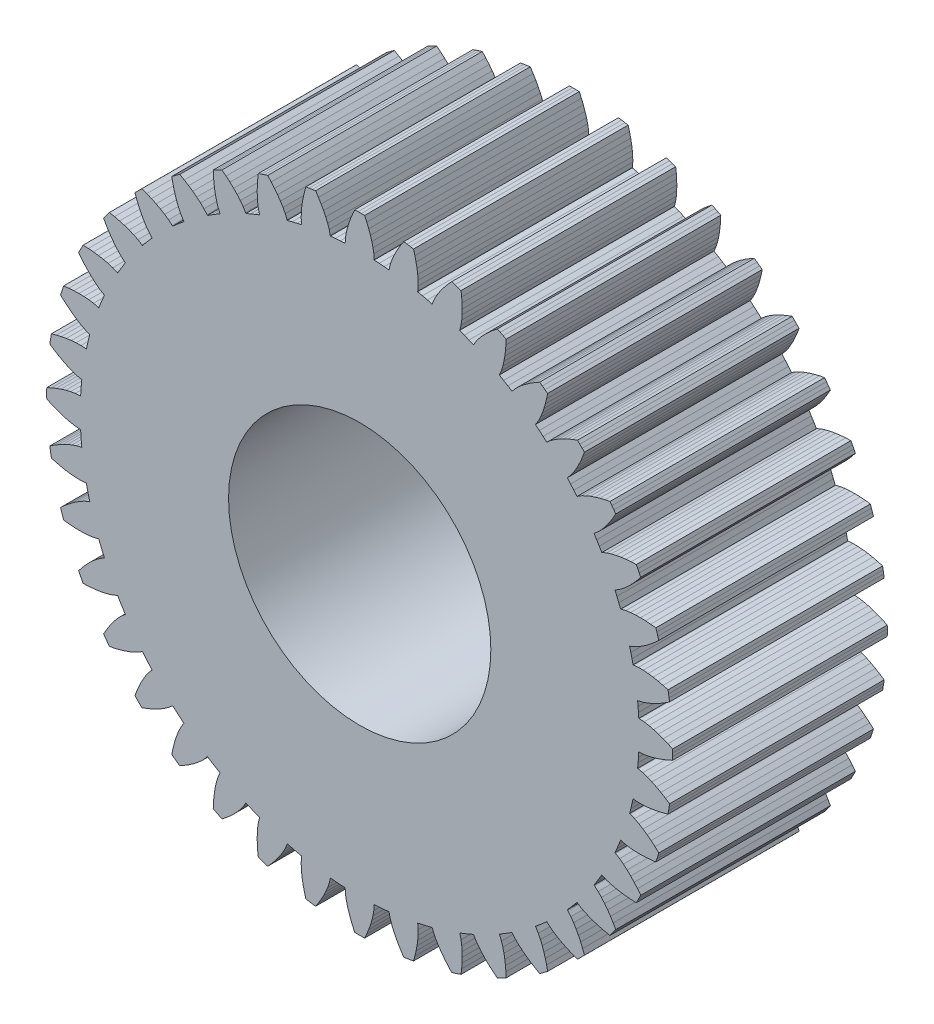
SolidWorks part; units mm, degrees
ref_plane "Спереди" through (0, 0, 0) normal (0, 0, 1) x (1, 0, 0)
ref_plane "Сверху" through (0, 0, 0) normal (0, 1, 0) x (1, 0, 0)
ref_plane "Справа" through (0, 0, 0) normal (1, 0, 0) x (0, 0, -1)
sketch "Эскиз1" plane through (0, 0, 0) normal (0, 0, 1) x (1, 0, 0)
  line L0 (23.4061, -1.2129) -> (23.4608, -1.2158)
  line L1 (23.4608, -1.2158) -> (23.8567, -1.1877)
  line L2 (23.8567, -1.1877) -> (24.2545, -1.1182)
  line L3 (24.2545, -1.1182) -> (24.6531, -1.0204)
  line L4 (24.6531, -1.0204) -> (25.052, -0.8989)
  line L5 (25.052, -0.8989) -> (25.4509, -0.7561)
  line L6 (25.4509, -0.7561) -> (25.8492, -0.5936)
  line L7 (25.8492, -0.5936) -> (26.2468, -0.4124)
  line L8 (26.2468, -0.4124) -> (26.2496, -0.1375)
  line L9 (26.2496, -0.1375) -> (26.2496, 0.1375)
  line L10 (26.2496, 0.1375) -> (26.2468, 0.4124)
  line L11 (26.2468, 0.4124) -> (25.8492, 0.5936)
  line L12 (25.8492, 0.5936) -> (25.4509, 0.7561)
  line L13 (25.4509, 0.7561) -> (25.052, 0.8989)
  line L14 (25.052, 0.8989) -> (24.6531, 1.0204)
  line L15 (24.6531, 1.0204) -> (24.2545, 1.1182)
  line L16 (24.2545, 1.1182) -> (23.8567, 1.1877)
  line L17 (23.8567, 1.1877) -> (23.4608, 1.2158)
  line L18 (23.4608, 1.2158) -> (23.4061, 1.2129)
  line L19 (23.4061, 1.2129) -> (23.3807, 1.6304)
  line L20 (23.3807, 1.6304) -> (23.3479, 2.0473)
  line L21 (23.3479, 2.0473) -> (23.3077, 2.4635)
  line L22 (23.3077, 2.4635) -> (23.3622, 2.4693)
  line L23 (23.3622, 2.4693) -> (23.7488, 2.559)
  line L24 (23.7488, 2.559) -> (24.1308, 2.6898)
  line L25 (24.1308, 2.6898) -> (24.5092, 2.8487)
  line L26 (24.5092, 2.8487) -> (24.8842, 3.0311)
  line L27 (24.8842, 3.0311) -> (25.2558, 3.2346)
  line L28 (25.2558, 3.2346) -> (25.6238, 3.4574)
  line L29 (25.6238, 3.4574) -> (25.9881, 3.6986)
  line L30 (25.9881, 3.6986) -> (25.948, 3.9706)
  line L31 (25.948, 3.9706) -> (25.905, 4.2421)
  line L32 (25.905, 4.2421) -> (25.8591, 4.5132)
  line L33 (25.8591, 4.5132) -> (25.4381, 4.63)
  line L34 (25.4381, 4.63) -> (25.0192, 4.7282)
  line L35 (25.0192, 4.7282) -> (24.603, 4.8069)
  line L36 (24.603, 4.8069) -> (24.1899, 4.8645)
  line L37 (24.1899, 4.8645) -> (23.7809, 4.8986)
  line L38 (23.7809, 4.8986) -> (23.3772, 4.9051)
  line L39 (23.3772, 4.9051) -> (22.9818, 4.8709)
  line L40 (22.9818, 4.8709) -> (22.9282, 4.8595)
  line L41 (22.9282, 4.8595) -> (22.8378, 5.2678)
  line L42 (22.8378, 5.2678) -> (22.7402, 5.6745)
  line L43 (22.7402, 5.6745) -> (22.6353, 6.0793)
  line L44 (22.6353, 6.0793) -> (22.6883, 6.0935)
  line L45 (22.6883, 6.0935) -> (23.0561, 6.2426)
  line L46 (23.0561, 6.2426) -> (23.4129, 6.4316)
  line L47 (23.4129, 6.4316) -> (23.7618, 6.6477)
  line L48 (23.7618, 6.6477) -> (24.1037, 6.8865)
  line L49 (24.1037, 6.8865) -> (24.4389, 7.1456)
  line L50 (24.4389, 7.1456) -> (24.7675, 7.4233)
  line L51 (24.7675, 7.4233) -> (25.0896, 7.7185)
  line L52 (25.0896, 7.7185) -> (25.0074, 7.9808)
  line L53 (25.0074, 7.9808) -> (24.9224, 8.2423)
  line L54 (24.9224, 8.2423) -> (24.8347, 8.5029)
  line L55 (24.8347, 8.5029) -> (24.4007, 8.5524)
  line L56 (24.4007, 8.5524) -> (23.9715, 8.5839)
  line L57 (23.9715, 8.5839) -> (23.5481, 8.5964)
  line L58 (23.5481, 8.5964) -> (23.1311, 8.5887)
  line L59 (23.1311, 8.5887) -> (22.7218, 8.5585)
  line L60 (22.7218, 8.5585) -> (22.3221, 8.5017)
  line L61 (22.3221, 8.5017) -> (21.9369, 8.406)
  line L62 (21.9369, 8.406) -> (21.8857, 8.3864)
  line L63 (21.8857, 8.3864) -> (21.7326, 8.7756)
  line L64 (21.7326, 8.7756) -> (21.5725, 9.162)
  line L65 (21.5725, 9.162) -> (21.4056, 9.5454)
  line L66 (21.4056, 9.5454) -> (21.4557, 9.5678)
  line L67 (21.4557, 9.5678) -> (21.7957, 9.7725)
  line L68 (21.7957, 9.7725) -> (22.1185, 10.015)
  line L69 (22.1185, 10.015) -> (22.4293, 10.283)
  line L70 (22.4293, 10.283) -> (22.7296, 10.5724)
  line L71 (22.7296, 10.5724) -> (23.0202, 10.8807)
  line L72 (23.0202, 10.8807) -> (23.3013, 11.2064)
  line L73 (23.3013, 11.2064) -> (23.5733, 11.5483)
  line L74 (23.5733, 11.5483) -> (23.451, 11.7946)
  line L75 (23.451, 11.7946) -> (23.3262, 12.0396)
  line L76 (23.3262, 12.0396) -> (23.1988, 12.2832)
  line L77 (23.1988, 12.2832) -> (22.7624, 12.2642)
  line L78 (22.7624, 12.2642) -> (22.3336, 12.2282)
  line L79 (22.3336, 12.2282) -> (21.9134, 12.1743)
  line L80 (21.9134, 12.1743) -> (21.5028, 12.1015)
  line L81 (21.5028, 12.1015) -> (21.1032, 12.0076)
  line L82 (21.1032, 12.0076) -> (20.7173, 11.8889)
  line L83 (20.7173, 11.8889) -> (20.3518, 11.7342)
  line L84 (20.3518, 11.7342) -> (20.3043, 11.7069)
  line L85 (20.3043, 11.7069) -> (20.0922, 12.0673)
  line L86 (20.0922, 12.0673) -> (19.8737, 12.4239)
  line L87 (19.8737, 12.4239) -> (19.6489, 12.7765)
  line L88 (19.6489, 12.7765) -> (19.6948, 12.8064)
  line L89 (19.6948, 12.8064) -> (19.9986, 13.0618)
  line L90 (19.9986, 13.0618) -> (20.2795, 13.3518)
  line L91 (20.2795, 13.3518) -> (20.5446, 13.6652)
  line L92 (20.5446, 13.6652) -> (20.7959, 13.9979)
  line L93 (20.7959, 13.9979) -> (21.0346, 14.3479)
  line L94 (21.0346, 14.3479) -> (21.2614, 14.7136)
  line L95 (21.2614, 14.7136) -> (21.4765, 15.0938)
  line L96 (21.4765, 15.0938) -> (21.3172, 15.3179)
  line L97 (21.3172, 15.3179) -> (21.1556, 15.5404)
  line L98 (21.1556, 15.5404) -> (20.9917, 15.7611)
  line L99 (20.9917, 15.7611) -> (20.5636, 15.674)
  line L100 (20.5636, 15.674) -> (20.1457, 15.5714)
  line L101 (20.1457, 15.5714) -> (19.7391, 15.4525)
  line L102 (19.7391, 15.4525) -> (19.345, 15.3163)
  line L103 (19.345, 15.3163) -> (18.965, 15.161)
  line L104 (18.965, 15.161) -> (18.6024, 14.9835)
  line L105 (18.6024, 14.9835) -> (18.2656, 14.7735)
  line L106 (18.2656, 14.7735) -> (18.223, 14.739)
  line L107 (18.223, 14.739) -> (17.9571, 15.0618)
  line L108 (17.9571, 15.0618) -> (17.6855, 15.3798)
  line L109 (17.6855, 15.3798) -> (17.4083, 15.6929)
  line L110 (17.4083, 15.6929) -> (17.449, 15.7296)
  line L111 (17.449, 15.7296) -> (17.7091, 16.0294)
  line L112 (17.7091, 16.0294) -> (17.9412, 16.3598)
  line L113 (17.9412, 16.3598) -> (18.1539, 16.7108)
  line L114 (18.1539, 16.7108) -> (18.3501, 17.0788)
  line L115 (18.3501, 17.0788) -> (18.5311, 17.4618)
  line L116 (18.5311, 17.4618) -> (18.6979, 17.8584)
  line L117 (18.6979, 17.8584) -> (18.8509, 18.2677)
  line L118 (18.8509, 18.2677) -> (18.6585, 18.4641)
  line L119 (18.6585, 18.4641) -> (18.4641, 18.6585)
  line L120 (18.4641, 18.6585) -> (18.2677, 18.8509)
  line L121 (18.2677, 18.8509) -> (17.8584, 18.6979)
  line L122 (17.8584, 18.6979) -> (17.4618, 18.5311)
  line L123 (17.4618, 18.5311) -> (17.0788, 18.3501)
  line L124 (17.0788, 18.3501) -> (16.7108, 18.1539)
  line L125 (16.7108, 18.1539) -> (16.3598, 17.9412)
  line L126 (16.3598, 17.9412) -> (16.0294, 17.7091)
  line L127 (16.0294, 17.7091) -> (15.7296, 17.449)
  line L128 (15.7296, 17.449) -> (15.6929, 17.4083)
  line L129 (15.6929, 17.4083) -> (15.3798, 17.6855)
  line L130 (15.3798, 17.6855) -> (15.0618, 17.9571)
  line L131 (15.0618, 17.9571) -> (14.739, 18.223)
  line L132 (14.739, 18.223) -> (14.7735, 18.2656)
  line L133 (14.7735, 18.2656) -> (14.9835, 18.6024)
  line L134 (14.9835, 18.6024) -> (15.161, 18.965)
  line L135 (15.161, 18.965) -> (15.3163, 19.345)
  line L136 (15.3163, 19.345) -> (15.4525, 19.7391)
  line L137 (15.4525, 19.7391) -> (15.5714, 20.1457)
  line L138 (15.5714, 20.1457) -> (15.674, 20.5636)
  line L139 (15.674, 20.5636) -> (15.7611, 20.9917)
  line L140 (15.7611, 20.9917) -> (15.5404, 21.1556)
  line L141 (15.5404, 21.1556) -> (15.3179, 21.3172)
  line L142 (15.3179, 21.3172) -> (15.0938, 21.4765)
  line L143 (15.0938, 21.4765) -> (14.7136, 21.2614)
  line L144 (14.7136, 21.2614) -> (14.3479, 21.0346)
  line L145 (14.3479, 21.0346) -> (13.9979, 20.7959)
  line L146 (13.9979, 20.7959) -> (13.6652, 20.5446)
  line L147 (13.6652, 20.5446) -> (13.3518, 20.2795)
  line L148 (13.3518, 20.2795) -> (13.0618, 19.9986)
  line L149 (13.0618, 19.9986) -> (12.8064, 19.6948)
  line L150 (12.8064, 19.6948) -> (12.7765, 19.6489)
  line L151 (12.7765, 19.6489) -> (12.4239, 19.8737)
  line L152 (12.4239, 19.8737) -> (12.0673, 20.0922)
  line L153 (12.0673, 20.0922) -> (11.7069, 20.3043)
  line L154 (11.7069, 20.3043) -> (11.7342, 20.3518)
  line L155 (11.7342, 20.3518) -> (11.8889, 20.7173)
  line L156 (11.8889, 20.7173) -> (12.0076, 21.1032)
  line L157 (12.0076, 21.1032) -> (12.1015, 21.5028)
  line L158 (12.1015, 21.5028) -> (12.1743, 21.9134)
  line L159 (12.1743, 21.9134) -> (12.2282, 22.3336)
  line L160 (12.2282, 22.3336) -> (12.2642, 22.7624)
  line L161 (12.2642, 22.7624) -> (12.2832, 23.1988)
  line L162 (12.2832, 23.1988) -> (12.0396, 23.3262)
  line L163 (12.0396, 23.3262) -> (11.7946, 23.451)
  line L164 (11.7946, 23.451) -> (11.5483, 23.5733)
  line L165 (11.5483, 23.5733) -> (11.2064, 23.3013)
  line L166 (11.2064, 23.3013) -> (10.8807, 23.0202)
  line L167 (10.8807, 23.0202) -> (10.5724, 22.7296)
  line L168 (10.5724, 22.7296) -> (10.283, 22.4293)
  line L169 (10.283, 22.4293) -> (10.015, 22.1185)
  line L170 (10.015, 22.1185) -> (9.7725, 21.7957)
  line L171 (9.7725, 21.7957) -> (9.5678, 21.4557)
  line L172 (9.5678, 21.4557) -> (9.5454, 21.4056)
  line L173 (9.5454, 21.4056) -> (9.162, 21.5725)
  line L174 (9.162, 21.5725) -> (8.7756, 21.7326)
  line L175 (8.7756, 21.7326) -> (8.3864, 21.8857)
  line L176 (8.3864, 21.8857) -> (8.406, 21.9369)
  line L177 (8.406, 21.9369) -> (8.5017, 22.3221)
  line L178 (8.5017, 22.3221) -> (8.5585, 22.7218)
  line L179 (8.5585, 22.7218) -> (8.5887, 23.1311)
  line L180 (8.5887, 23.1311) -> (8.5964, 23.5481)
  line L181 (8.5964, 23.5481) -> (8.5839, 23.9715)
  line L182 (8.5839, 23.9715) -> (8.5524, 24.4007)
  line L183 (8.5524, 24.4007) -> (8.5029, 24.8347)
  line L184 (8.5029, 24.8347) -> (8.2423, 24.9224)
  line L185 (8.2423, 24.9224) -> (7.9808, 25.0074)
  line L186 (7.9808, 25.0074) -> (7.7185, 25.0896)
  line L187 (7.7185, 25.0896) -> (7.4233, 24.7675)
  line L188 (7.4233, 24.7675) -> (7.1456, 24.4389)
  line L189 (7.1456, 24.4389) -> (6.8865, 24.1037)
  line L190 (6.8865, 24.1037) -> (6.6477, 23.7618)
  line L191 (6.6477, 23.7618) -> (6.4316, 23.4129)
  line L192 (6.4316, 23.4129) -> (6.2426, 23.0561)
  line L193 (6.2426, 23.0561) -> (6.0935, 22.6883)
  line L194 (6.0935, 22.6883) -> (6.0793, 22.6353)
  line L195 (6.0793, 22.6353) -> (5.6745, 22.7402)
  line L196 (5.6745, 22.7402) -> (5.2678, 22.8378)
  line L197 (5.2678, 22.8378) -> (4.8595, 22.9282)
  line L198 (4.8595, 22.9282) -> (4.8709, 22.9818)
  line L199 (4.8709, 22.9818) -> (4.9051, 23.3772)
  line L200 (4.9051, 23.3772) -> (4.8986, 23.7809)
  line L201 (4.8986, 23.7809) -> (4.8645, 24.1899)
  line L202 (4.8645, 24.1899) -> (4.8069, 24.603)
  line L203 (4.8069, 24.603) -> (4.7282, 25.0192)
  line L204 (4.7282, 25.0192) -> (4.63, 25.4381)
  line L205 (4.63, 25.4381) -> (4.5132, 25.8591)
  line L206 (4.5132, 25.8591) -> (4.2421, 25.905)
  line L207 (4.2421, 25.905) -> (3.9706, 25.948)
  line L208 (3.9706, 25.948) -> (3.6986, 25.9881)
  line L209 (3.6986, 25.9881) -> (3.4574, 25.6238)
  line L210 (3.4574, 25.6238) -> (3.2346, 25.2558)
  line L211 (3.2346, 25.2558) -> (3.0311, 24.8842)
  line L212 (3.0311, 24.8842) -> (2.8487, 24.5092)
  line L213 (2.8487, 24.5092) -> (2.6898, 24.1308)
  line L214 (2.6898, 24.1308) -> (2.559, 23.7488)
  line L215 (2.559, 23.7488) -> (2.4693, 23.3622)
  line L216 (2.4693, 23.3622) -> (2.4635, 23.3077)
  line L217 (2.4635, 23.3077) -> (2.0473, 23.3479)
  line L218 (2.0473, 23.3479) -> (1.6304, 23.3807)
  line L219 (1.6304, 23.3807) -> (1.2129, 23.4061)
  line L220 (1.2129, 23.4061) -> (1.2158, 23.4608)
  line L221 (1.2158, 23.4608) -> (1.1877, 23.8567)
  line L222 (1.1877, 23.8567) -> (1.1182, 24.2545)
  line L223 (1.1182, 24.2545) -> (1.0204, 24.6531)
  line L224 (1.0204, 24.6531) -> (0.8989, 25.052)
  line L225 (0.8989, 25.052) -> (0.7561, 25.4509)
  line L226 (0.7561, 25.4509) -> (0.5936, 25.8492)
  line L227 (0.5936, 25.8492) -> (0.4124, 26.2468)
  line L228 (0.4124, 26.2468) -> (0.1375, 26.2496)
  line L229 (0.1375, 26.2496) -> (-0.1375, 26.2496)
  line L230 (-0.1375, 26.2496) -> (-0.4124, 26.2468)
  line L231 (-0.4124, 26.2468) -> (-0.5936, 25.8492)
  line L232 (-0.5936, 25.8492) -> (-0.7561, 25.4509)
  line L233 (-0.7561, 25.4509) -> (-0.8989, 25.052)
  line L234 (-0.8989, 25.052) -> (-1.0204, 24.6531)
  line L235 (-1.0204, 24.6531) -> (-1.1182, 24.2545)
  line L236 (-1.1182, 24.2545) -> (-1.1877, 23.8567)
  line L237 (-1.1877, 23.8567) -> (-1.2158, 23.4608)
  line L238 (-1.2158, 23.4608) -> (-1.2129, 23.4061)
  line L239 (-1.2129, 23.4061) -> (-1.6304, 23.3807)
  line L240 (-1.6304, 23.3807) -> (-2.0473, 23.3479)
  line L241 (-2.0473, 23.3479) -> (-2.4635, 23.3077)
  line L242 (-2.4635, 23.3077) -> (-2.4693, 23.3622)
  line L243 (-2.4693, 23.3622) -> (-2.559, 23.7488)
  line L244 (-2.559, 23.7488) -> (-2.6898, 24.1308)
  line L245 (-2.6898, 24.1308) -> (-2.8487, 24.5092)
  line L246 (-2.8487, 24.5092) -> (-3.0311, 24.8842)
  line L247 (-3.0311, 24.8842) -> (-3.2346, 25.2558)
  line L248 (-3.2346, 25.2558) -> (-3.4574, 25.6238)
  line L249 (-3.4574, 25.6238) -> (-3.6986, 25.9881)
  line L250 (-3.6986, 25.9881) -> (-3.9706, 25.948)
  line L251 (-3.9706, 25.948) -> (-4.2421, 25.905)
  line L252 (-4.2421, 25.905) -> (-4.5132, 25.8591)
  line L253 (-4.5132, 25.8591) -> (-4.63, 25.4381)
  line L254 (-4.63, 25.4381) -> (-4.7282, 25.0192)
  line L255 (-4.7282, 25.0192) -> (-4.8069, 24.603)
  line L256 (-4.8069, 24.603) -> (-4.8645, 24.1899)
  line L257 (-4.8645, 24.1899) -> (-4.8986, 23.7809)
  line L258 (-4.8986, 23.7809) -> (-4.9051, 23.3772)
  line L259 (-4.9051, 23.3772) -> (-4.8709, 22.9818)
  line L260 (-4.8709, 22.9818) -> (-4.8595, 22.9282)
  line L261 (-4.8595, 22.9282) -> (-5.2678, 22.8378)
  line L262 (-5.2678, 22.8378) -> (-5.6745, 22.7402)
  line L263 (-5.6745, 22.7402) -> (-6.0793, 22.6353)
  line L264 (-6.0793, 22.6353) -> (-6.0935, 22.6883)
  line L265 (-6.0935, 22.6883) -> (-6.2426, 23.0561)
  line L266 (-6.2426, 23.0561) -> (-6.4316, 23.4129)
  line L267 (-6.4316, 23.4129) -> (-6.6477, 23.7618)
  line L268 (-6.6477, 23.7618) -> (-6.8865, 24.1037)
  line L269 (-6.8865, 24.1037) -> (-7.1456, 24.4389)
  line L270 (-7.1456, 24.4389) -> (-7.4233, 24.7675)
  line L271 (-7.4233, 24.7675) -> (-7.7185, 25.0896)
  line L272 (-7.7185, 25.0896) -> (-7.9808, 25.0074)
  line L273 (-7.9808, 25.0074) -> (-8.2423, 24.9224)
  line L274 (-8.2423, 24.9224) -> (-8.5029, 24.8347)
  line L275 (-8.5029, 24.8347) -> (-8.5524, 24.4007)
  line L276 (-8.5524, 24.4007) -> (-8.5839, 23.9715)
  line L277 (-8.5839, 23.9715) -> (-8.5964, 23.5481)
  line L278 (-8.5964, 23.5481) -> (-8.5887, 23.1311)
  line L279 (-8.5887, 23.1311) -> (-8.5585, 22.7218)
  line L280 (-8.5585, 22.7218) -> (-8.5017, 22.3221)
  line L281 (-8.5017, 22.3221) -> (-8.406, 21.9369)
  line L282 (-8.406, 21.9369) -> (-8.3864, 21.8857)
  line L283 (-8.3864, 21.8857) -> (-8.7756, 21.7326)
  line L284 (-8.7756, 21.7326) -> (-9.162, 21.5725)
  line L285 (-9.162, 21.5725) -> (-9.5454, 21.4056)
  line L286 (-9.5454, 21.4056) -> (-9.5678, 21.4557)
  line L287 (-9.5678, 21.4557) -> (-9.7725, 21.7957)
  line L288 (-9.7725, 21.7957) -> (-10.015, 22.1185)
  line L289 (-10.015, 22.1185) -> (-10.283, 22.4293)
  line L290 (-10.283, 22.4293) -> (-10.5724, 22.7296)
  line L291 (-10.5724, 22.7296) -> (-10.8807, 23.0202)
  line L292 (-10.8807, 23.0202) -> (-11.2064, 23.3013)
  line L293 (-11.2064, 23.3013) -> (-11.5483, 23.5733)
  line L294 (-11.5483, 23.5733) -> (-11.7946, 23.451)
  line L295 (-11.7946, 23.451) -> (-12.0396, 23.3262)
  line L296 (-12.0396, 23.3262) -> (-12.2832, 23.1988)
  line L297 (-12.2832, 23.1988) -> (-12.2642, 22.7624)
  line L298 (-12.2642, 22.7624) -> (-12.2282, 22.3336)
  line L299 (-12.2282, 22.3336) -> (-12.1743, 21.9134)
  line L300 (-12.1743, 21.9134) -> (-12.1015, 21.5028)
  line L301 (-12.1015, 21.5028) -> (-12.0076, 21.1032)
  line L302 (-12.0076, 21.1032) -> (-11.8889, 20.7173)
  line L303 (-11.8889, 20.7173) -> (-11.7342, 20.3518)
  line L304 (-11.7342, 20.3518) -> (-11.7069, 20.3043)
  line L305 (-11.7069, 20.3043) -> (-12.0673, 20.0922)
  line L306 (-12.0673, 20.0922) -> (-12.4239, 19.8737)
  line L307 (-12.4239, 19.8737) -> (-12.7765, 19.6489)
  line L308 (-12.7765, 19.6489) -> (-12.8064, 19.6948)
  line L309 (-12.8064, 19.6948) -> (-13.0618, 19.9986)
  line L310 (-13.0618, 19.9986) -> (-13.3518, 20.2795)
  line L311 (-13.3518, 20.2795) -> (-13.6652, 20.5446)
  line L312 (-13.6652, 20.5446) -> (-13.9979, 20.7959)
  line L313 (-13.9979, 20.7959) -> (-14.3479, 21.0346)
  line L314 (-14.3479, 21.0346) -> (-14.7136, 21.2614)
  line L315 (-14.7136, 21.2614) -> (-15.0938, 21.4765)
  line L316 (-15.0938, 21.4765) -> (-15.3179, 21.3172)
  line L317 (-15.3179, 21.3172) -> (-15.5404, 21.1556)
  line L318 (-15.5404, 21.1556) -> (-15.7611, 20.9917)
  line L319 (-15.7611, 20.9917) -> (-15.674, 20.5636)
  line L320 (-15.674, 20.5636) -> (-15.5714, 20.1457)
  line L321 (-15.5714, 20.1457) -> (-15.4525, 19.7391)
  line L322 (-15.4525, 19.7391) -> (-15.3163, 19.345)
  line L323 (-15.3163, 19.345) -> (-15.161, 18.965)
  line L324 (-15.161, 18.965) -> (-14.9835, 18.6024)
  line L325 (-14.9835, 18.6024) -> (-14.7735, 18.2656)
  line L326 (-14.7735, 18.2656) -> (-14.739, 18.223)
  line L327 (-14.739, 18.223) -> (-15.0618, 17.9571)
  line L328 (-15.0618, 17.9571) -> (-15.3798, 17.6855)
  line L329 (-15.3798, 17.6855) -> (-15.6929, 17.4083)
  line L330 (-15.6929, 17.4083) -> (-15.7296, 17.449)
  line L331 (-15.7296, 17.449) -> (-16.0294, 17.7091)
  line L332 (-16.0294, 17.7091) -> (-16.3598, 17.9412)
  line L333 (-16.3598, 17.9412) -> (-16.7108, 18.1539)
  line L334 (-16.7108, 18.1539) -> (-17.0788, 18.3501)
  line L335 (-17.0788, 18.3501) -> (-17.4618, 18.5311)
  line L336 (-17.4618, 18.5311) -> (-17.8584, 18.6979)
  line L337 (-17.8584, 18.6979) -> (-18.2677, 18.8509)
  line L338 (-18.2677, 18.8509) -> (-18.4641, 18.6585)
  line L339 (-18.4641, 18.6585) -> (-18.6585, 18.4641)
  line L340 (-18.6585, 18.4641) -> (-18.8509, 18.2677)
  line L341 (-18.8509, 18.2677) -> (-18.6979, 17.8584)
  line L342 (-18.6979, 17.8584) -> (-18.5311, 17.4618)
  line L343 (-18.5311, 17.4618) -> (-18.3501, 17.0788)
  line L344 (-18.3501, 17.0788) -> (-18.1539, 16.7108)
  line L345 (-18.1539, 16.7108) -> (-17.9412, 16.3598)
  line L346 (-17.9412, 16.3598) -> (-17.7091, 16.0294)
  line L347 (-17.7091, 16.0294) -> (-17.449, 15.7296)
  line L348 (-17.449, 15.7296) -> (-17.4083, 15.6929)
  line L349 (-17.4083, 15.6929) -> (-17.6855, 15.3798)
  line L350 (-17.6855, 15.3798) -> (-17.9571, 15.0618)
  line L351 (-17.9571, 15.0618) -> (-18.223, 14.739)
  line L352 (-18.223, 14.739) -> (-18.2656, 14.7735)
  line L353 (-18.2656, 14.7735) -> (-18.6024, 14.9835)
  line L354 (-18.6024, 14.9835) -> (-18.965, 15.161)
  line L355 (-18.965, 15.161) -> (-19.345, 15.3163)
  line L356 (-19.345, 15.3163) -> (-19.7391, 15.4525)
  line L357 (-19.7391, 15.4525) -> (-20.1457, 15.5714)
  line L358 (-20.1457, 15.5714) -> (-20.5636, 15.674)
  line L359 (-20.5636, 15.674) -> (-20.9917, 15.7611)
  line L360 (-20.9917, 15.7611) -> (-21.1556, 15.5404)
  line L361 (-21.1556, 15.5404) -> (-21.3172, 15.3179)
  line L362 (-21.3172, 15.3179) -> (-21.4765, 15.0938)
  line L363 (-21.4765, 15.0938) -> (-21.2614, 14.7136)
  line L364 (-21.2614, 14.7136) -> (-21.0346, 14.3479)
  line L365 (-21.0346, 14.3479) -> (-20.7959, 13.9979)
  line L366 (-20.7959, 13.9979) -> (-20.5446, 13.6652)
  line L367 (-20.5446, 13.6652) -> (-20.2795, 13.3518)
  line L368 (-20.2795, 13.3518) -> (-19.9986, 13.0618)
  line L369 (-19.9986, 13.0618) -> (-19.6948, 12.8064)
  line L370 (-19.6948, 12.8064) -> (-19.6489, 12.7765)
  line L371 (-19.6489, 12.7765) -> (-19.8737, 12.4239)
  line L372 (-19.8737, 12.4239) -> (-20.0922, 12.0673)
  line L373 (-20.0922, 12.0673) -> (-20.3043, 11.7069)
  line L374 (-20.3043, 11.7069) -> (-20.3518, 11.7342)
  line L375 (-20.3518, 11.7342) -> (-20.7173, 11.8889)
  line L376 (-20.7173, 11.8889) -> (-21.1032, 12.0076)
  line L377 (-21.1032, 12.0076) -> (-21.5028, 12.1015)
  line L378 (-21.5028, 12.1015) -> (-21.9134, 12.1743)
  line L379 (-21.9134, 12.1743) -> (-22.3336, 12.2282)
  line L380 (-22.3336, 12.2282) -> (-22.7624, 12.2642)
  line L381 (-22.7624, 12.2642) -> (-23.1988, 12.2832)
  line L382 (-23.1988, 12.2832) -> (-23.3262, 12.0396)
  line L383 (-23.3262, 12.0396) -> (-23.451, 11.7946)
  line L384 (-23.451, 11.7946) -> (-23.5733, 11.5483)
  line L385 (-23.5733, 11.5483) -> (-23.3013, 11.2064)
  line L386 (-23.3013, 11.2064) -> (-23.0202, 10.8807)
  line L387 (-23.0202, 10.8807) -> (-22.7296, 10.5724)
  line L388 (-22.7296, 10.5724) -> (-22.4293, 10.283)
  line L389 (-22.4293, 10.283) -> (-22.1185, 10.015)
  line L390 (-22.1185, 10.015) -> (-21.7957, 9.7725)
  line L391 (-21.7957, 9.7725) -> (-21.4557, 9.5678)
  line L392 (-21.4557, 9.5678) -> (-21.4056, 9.5454)
  line L393 (-21.4056, 9.5454) -> (-21.5725, 9.162)
  line L394 (-21.5725, 9.162) -> (-21.7326, 8.7756)
  line L395 (-21.7326, 8.7756) -> (-21.8857, 8.3864)
  line L396 (-21.8857, 8.3864) -> (-21.9369, 8.406)
  line L397 (-21.9369, 8.406) -> (-22.3221, 8.5017)
  line L398 (-22.3221, 8.5017) -> (-22.7218, 8.5585)
  line L399 (-22.7218, 8.5585) -> (-23.1311, 8.5887)
  line L400 (-23.1311, 8.5887) -> (-23.5481, 8.5964)
  line L401 (-23.5481, 8.5964) -> (-23.9715, 8.5839)
  line L402 (-23.9715, 8.5839) -> (-24.4007, 8.5524)
  line L403 (-24.4007, 8.5524) -> (-24.8347, 8.5029)
  line L404 (-24.8347, 8.5029) -> (-24.9224, 8.2423)
  line L405 (-24.9224, 8.2423) -> (-25.0074, 7.9808)
  line L406 (-25.0074, 7.9808) -> (-25.0896, 7.7185)
  line L407 (-25.0896, 7.7185) -> (-24.7675, 7.4233)
  line L408 (-24.7675, 7.4233) -> (-24.4389, 7.1456)
  line L409 (-24.4389, 7.1456) -> (-24.1037, 6.8865)
  line L410 (-24.1037, 6.8865) -> (-23.7618, 6.6477)
  line L411 (-23.7618, 6.6477) -> (-23.4129, 6.4316)
  line L412 (-23.4129, 6.4316) -> (-23.0561, 6.2426)
  line L413 (-23.0561, 6.2426) -> (-22.6883, 6.0935)
  line L414 (-22.6883, 6.0935) -> (-22.6353, 6.0793)
  line L415 (-22.6353, 6.0793) -> (-22.7402, 5.6745)
  line L416 (-22.7402, 5.6745) -> (-22.8378, 5.2678)
  line L417 (-22.8378, 5.2678) -> (-22.9282, 4.8595)
  line L418 (-22.9282, 4.8595) -> (-22.9818, 4.8709)
  line L419 (-22.9818, 4.8709) -> (-23.3772, 4.9051)
  line L420 (-23.3772, 4.9051) -> (-23.7809, 4.8986)
  line L421 (-23.7809, 4.8986) -> (-24.1899, 4.8645)
  line L422 (-24.1899, 4.8645) -> (-24.603, 4.8069)
  line L423 (-24.603, 4.8069) -> (-25.0192, 4.7282)
  line L424 (-25.0192, 4.7282) -> (-25.4381, 4.63)
  line L425 (-25.4381, 4.63) -> (-25.8591, 4.5132)
  line L426 (-25.8591, 4.5132) -> (-25.905, 4.2421)
  line L427 (-25.905, 4.2421) -> (-25.948, 3.9706)
  line L428 (-25.948, 3.9706) -> (-25.9881, 3.6986)
  line L429 (-25.9881, 3.6986) -> (-25.6238, 3.4574)
  line L430 (-25.6238, 3.4574) -> (-25.2558, 3.2346)
  line L431 (-25.2558, 3.2346) -> (-24.8842, 3.0311)
  line L432 (-24.8842, 3.0311) -> (-24.5092, 2.8487)
  line L433 (-24.5092, 2.8487) -> (-24.1308, 2.6898)
  line L434 (-24.1308, 2.6898) -> (-23.7488, 2.559)
  line L435 (-23.7488, 2.559) -> (-23.3622, 2.4693)
  line L436 (-23.3622, 2.4693) -> (-23.3077, 2.4635)
  line L437 (-23.3077, 2.4635) -> (-23.3479, 2.0473)
  line L438 (-23.3479, 2.0473) -> (-23.3807, 1.6304)
  line L439 (-23.3807, 1.6304) -> (-23.4061, 1.2129)
  line L440 (-23.4061, 1.2129) -> (-23.4608, 1.2158)
  line L441 (-23.4608, 1.2158) -> (-23.8567, 1.1877)
  line L442 (-23.8567, 1.1877) -> (-24.2545, 1.1182)
  line L443 (-24.2545, 1.1182) -> (-24.6531, 1.0204)
  line L444 (-24.6531, 1.0204) -> (-25.052, 0.8989)
  line L445 (-25.052, 0.8989) -> (-25.4509, 0.7561)
  line L446 (-25.4509, 0.7561) -> (-25.8492, 0.5936)
  line L447 (-25.8492, 0.5936) -> (-26.2468, 0.4124)
  line L448 (-26.2468, 0.4124) -> (-26.2496, 0.1375)
  line L449 (-26.2496, 0.1375) -> (-26.2496, -0.1375)
  line L450 (-26.2496, -0.1375) -> (-26.2468, -0.4124)
  line L451 (-26.2468, -0.4124) -> (-25.8492, -0.5936)
  line L452 (-25.8492, -0.5936) -> (-25.4509, -0.7561)
  line L453 (-25.4509, -0.7561) -> (-25.052, -0.8989)
  line L454 (-25.052, -0.8989) -> (-24.6531, -1.0204)
  line L455 (-24.6531, -1.0204) -> (-24.2545, -1.1182)
  line L456 (-24.2545, -1.1182) -> (-23.8567, -1.1877)
  line L457 (-23.8567, -1.1877) -> (-23.4608, -1.2158)
  line L458 (-23.4608, -1.2158) -> (-23.4061, -1.2129)
  line L459 (-23.4061, -1.2129) -> (-23.3807, -1.6304)
  line L460 (-23.3807, -1.6304) -> (-23.3479, -2.0473)
  line L461 (-23.3479, -2.0473) -> (-23.3077, -2.4635)
  line L462 (-23.3077, -2.4635) -> (-23.3622, -2.4693)
  line L463 (-23.3622, -2.4693) -> (-23.7488, -2.559)
  line L464 (-23.7488, -2.559) -> (-24.1308, -2.6898)
  line L465 (-24.1308, -2.6898) -> (-24.5092, -2.8487)
  line L466 (-24.5092, -2.8487) -> (-24.8842, -3.0311)
  line L467 (-24.8842, -3.0311) -> (-25.2558, -3.2346)
  line L468 (-25.2558, -3.2346) -> (-25.6238, -3.4574)
  line L469 (-25.6238, -3.4574) -> (-25.9881, -3.6986)
  line L470 (-25.9881, -3.6986) -> (-25.948, -3.9706)
  line L471 (-25.948, -3.9706) -> (-25.905, -4.2421)
  line L472 (-25.905, -4.2421) -> (-25.8591, -4.5132)
  line L473 (-25.8591, -4.5132) -> (-25.4381, -4.63)
  line L474 (-25.4381, -4.63) -> (-25.0192, -4.7282)
  line L475 (-25.0192, -4.7282) -> (-24.603, -4.8069)
  line L476 (-24.603, -4.8069) -> (-24.1899, -4.8645)
  line L477 (-24.1899, -4.8645) -> (-23.7809, -4.8986)
  line L478 (-23.7809, -4.8986) -> (-23.3772, -4.9051)
  line L479 (-23.3772, -4.9051) -> (-22.9818, -4.8709)
  line L480 (-22.9818, -4.8709) -> (-22.9282, -4.8595)
  line L481 (-22.9282, -4.8595) -> (-22.8378, -5.2678)
  line L482 (-22.8378, -5.2678) -> (-22.7402, -5.6745)
  line L483 (-22.7402, -5.6745) -> (-22.6353, -6.0793)
  line L484 (-22.6353, -6.0793) -> (-22.6883, -6.0935)
  line L485 (-22.6883, -6.0935) -> (-23.0561, -6.2426)
  line L486 (-23.0561, -6.2426) -> (-23.4129, -6.4316)
  line L487 (-23.4129, -6.4316) -> (-23.7618, -6.6477)
  line L488 (-23.7618, -6.6477) -> (-24.1037, -6.8865)
  line L489 (-24.1037, -6.8865) -> (-24.4389, -7.1456)
  line L490 (-24.4389, -7.1456) -> (-24.7675, -7.4233)
  line L491 (-24.7675, -7.4233) -> (-25.0896, -7.7185)
  line L492 (-25.0896, -7.7185) -> (-25.0074, -7.9808)
  line L493 (-25.0074, -7.9808) -> (-24.9224, -8.2423)
  line L494 (-24.9224, -8.2423) -> (-24.8347, -8.5029)
  line L495 (-24.8347, -8.5029) -> (-24.4007, -8.5524)
  line L496 (-24.4007, -8.5524) -> (-23.9715, -8.5839)
  line L497 (-23.9715, -8.5839) -> (-23.5481, -8.5964)
  line L498 (-23.5481, -8.5964) -> (-23.1311, -8.5887)
  line L499 (-23.1311, -8.5887) -> (-22.7218, -8.5585)
  line L500 (-22.7218, -8.5585) -> (-22.3221, -8.5017)
  line L501 (-22.3221, -8.5017) -> (-21.9369, -8.406)
  line L502 (-21.9369, -8.406) -> (-21.8857, -8.3864)
  line L503 (-21.8857, -8.3864) -> (-21.7326, -8.7756)
  line L504 (-21.7326, -8.7756) -> (-21.5725, -9.162)
  line L505 (-21.5725, -9.162) -> (-21.4056, -9.5454)
  line L506 (-21.4056, -9.5454) -> (-21.4557, -9.5678)
  line L507 (-21.4557, -9.5678) -> (-21.7957, -9.7725)
  line L508 (-21.7957, -9.7725) -> (-22.1185, -10.015)
  line L509 (-22.1185, -10.015) -> (-22.4293, -10.283)
  line L510 (-22.4293, -10.283) -> (-22.7296, -10.5724)
  line L511 (-22.7296, -10.5724) -> (-23.0202, -10.8807)
  line L512 (-23.0202, -10.8807) -> (-23.3013, -11.2064)
  line L513 (-23.3013, -11.2064) -> (-23.5733, -11.5483)
  line L514 (-23.5733, -11.5483) -> (-23.451, -11.7946)
  line L515 (-23.451, -11.7946) -> (-23.3262, -12.0396)
  line L516 (-23.3262, -12.0396) -> (-23.1988, -12.2832)
  line L517 (-23.1988, -12.2832) -> (-22.7624, -12.2642)
  line L518 (-22.7624, -12.2642) -> (-22.3336, -12.2282)
  line L519 (-22.3336, -12.2282) -> (-21.9134, -12.1743)
  line L520 (-21.9134, -12.1743) -> (-21.5028, -12.1015)
  line L521 (-21.5028, -12.1015) -> (-21.1032, -12.0076)
  line L522 (-21.1032, -12.0076) -> (-20.7173, -11.8889)
  line L523 (-20.7173, -11.8889) -> (-20.3518, -11.7342)
  line L524 (-20.3518, -11.7342) -> (-20.3043, -11.7069)
  line L525 (-20.3043, -11.7069) -> (-20.0922, -12.0673)
  line L526 (-20.0922, -12.0673) -> (-19.8737, -12.4239)
  line L527 (-19.8737, -12.4239) -> (-19.6489, -12.7765)
  line L528 (-19.6489, -12.7765) -> (-19.6948, -12.8064)
  line L529 (-19.6948, -12.8064) -> (-19.9986, -13.0618)
  line L530 (-19.9986, -13.0618) -> (-20.2795, -13.3518)
  line L531 (-20.2795, -13.3518) -> (-20.5446, -13.6652)
  line L532 (-20.5446, -13.6652) -> (-20.7959, -13.9979)
  line L533 (-20.7959, -13.9979) -> (-21.0346, -14.3479)
  line L534 (-21.0346, -14.3479) -> (-21.2614, -14.7136)
  line L535 (-21.2614, -14.7136) -> (-21.4765, -15.0938)
  line L536 (-21.4765, -15.0938) -> (-21.3172, -15.3179)
  line L537 (-21.3172, -15.3179) -> (-21.1556, -15.5404)
  line L538 (-21.1556, -15.5404) -> (-20.9917, -15.7611)
  line L539 (-20.9917, -15.7611) -> (-20.5636, -15.674)
  line L540 (-20.5636, -15.674) -> (-20.1457, -15.5714)
  line L541 (-20.1457, -15.5714) -> (-19.7391, -15.4525)
  line L542 (-19.7391, -15.4525) -> (-19.345, -15.3163)
  line L543 (-19.345, -15.3163) -> (-18.965, -15.161)
  line L544 (-18.965, -15.161) -> (-18.6024, -14.9835)
  line L545 (-18.6024, -14.9835) -> (-18.2656, -14.7735)
  line L546 (-18.2656, -14.7735) -> (-18.223, -14.739)
  line L547 (-18.223, -14.739) -> (-17.9571, -15.0618)
  line L548 (-17.9571, -15.0618) -> (-17.6855, -15.3798)
  line L549 (-17.6855, -15.3798) -> (-17.4083, -15.6929)
  line L550 (-17.4083, -15.6929) -> (-17.449, -15.7296)
  line L551 (-17.449, -15.7296) -> (-17.7091, -16.0294)
  line L552 (-17.7091, -16.0294) -> (-17.9412, -16.3598)
  line L553 (-17.9412, -16.3598) -> (-18.1539, -16.7108)
  line L554 (-18.1539, -16.7108) -> (-18.3501, -17.0788)
  line L555 (-18.3501, -17.0788) -> (-18.5311, -17.4618)
  line L556 (-18.5311, -17.4618) -> (-18.6979, -17.8584)
  line L557 (-18.6979, -17.8584) -> (-18.8509, -18.2677)
  line L558 (-18.8509, -18.2677) -> (-18.6585, -18.4641)
  line L559 (-18.6585, -18.4641) -> (-18.4641, -18.6585)
  line L560 (-18.4641, -18.6585) -> (-18.2677, -18.8509)
  line L561 (-18.2677, -18.8509) -> (-17.8584, -18.6979)
  line L562 (-17.8584, -18.6979) -> (-17.4618, -18.5311)
  line L563 (-17.4618, -18.5311) -> (-17.0788, -18.3501)
  line L564 (-17.0788, -18.3501) -> (-16.7108, -18.1539)
  line L565 (-16.7108, -18.1539) -> (-16.3598, -17.9412)
  line L566 (-16.3598, -17.9412) -> (-16.0294, -17.7091)
  line L567 (-16.0294, -17.7091) -> (-15.7296, -17.449)
  line L568 (-15.7296, -17.449) -> (-15.6929, -17.4083)
  line L569 (-15.6929, -17.4083) -> (-15.3798, -17.6855)
  line L570 (-15.3798, -17.6855) -> (-15.0618, -17.9571)
  line L571 (-15.0618, -17.9571) -> (-14.739, -18.223)
  line L572 (-14.739, -18.223) -> (-14.7735, -18.2656)
  line L573 (-14.7735, -18.2656) -> (-14.9835, -18.6024)
  line L574 (-14.9835, -18.6024) -> (-15.161, -18.965)
  line L575 (-15.161, -18.965) -> (-15.3163, -19.345)
  line L576 (-15.3163, -19.345) -> (-15.4525, -19.7391)
  line L577 (-15.4525, -19.7391) -> (-15.5714, -20.1457)
  line L578 (-15.5714, -20.1457) -> (-15.674, -20.5636)
  line L579 (-15.674, -20.5636) -> (-15.7611, -20.9917)
  line L580 (-15.7611, -20.9917) -> (-15.5404, -21.1556)
  line L581 (-15.5404, -21.1556) -> (-15.3179, -21.3172)
  line L582 (-15.3179, -21.3172) -> (-15.0938, -21.4765)
  line L583 (-15.0938, -21.4765) -> (-14.7136, -21.2614)
  line L584 (-14.7136, -21.2614) -> (-14.3479, -21.0346)
  line L585 (-14.3479, -21.0346) -> (-13.9979, -20.7959)
  line L586 (-13.9979, -20.7959) -> (-13.6652, -20.5446)
  line L587 (-13.6652, -20.5446) -> (-13.3518, -20.2795)
  line L588 (-13.3518, -20.2795) -> (-13.0618, -19.9986)
  line L589 (-13.0618, -19.9986) -> (-12.8064, -19.6948)
  line L590 (-12.8064, -19.6948) -> (-12.7765, -19.6489)
  line L591 (-12.7765, -19.6489) -> (-12.4239, -19.8737)
  line L592 (-12.4239, -19.8737) -> (-12.0673, -20.0922)
  line L593 (-12.0673, -20.0922) -> (-11.7069, -20.3043)
  line L594 (-11.7069, -20.3043) -> (-11.7342, -20.3518)
  line L595 (-11.7342, -20.3518) -> (-11.8889, -20.7173)
  line L596 (-11.8889, -20.7173) -> (-12.0076, -21.1032)
  line L597 (-12.0076, -21.1032) -> (-12.1015, -21.5028)
  line L598 (-12.1015, -21.5028) -> (-12.1743, -21.9134)
  line L599 (-12.1743, -21.9134) -> (-12.2282, -22.3336)
  line L600 (-12.2282, -22.3336) -> (-12.2642, -22.7624)
  line L601 (-12.2642, -22.7624) -> (-12.2832, -23.1988)
  line L602 (-12.2832, -23.1988) -> (-12.0396, -23.3262)
  line L603 (-12.0396, -23.3262) -> (-11.7946, -23.451)
  line L604 (-11.7946, -23.451) -> (-11.5483, -23.5733)
  line L605 (-11.5483, -23.5733) -> (-11.2064, -23.3013)
  line L606 (-11.2064, -23.3013) -> (-10.8807, -23.0202)
  line L607 (-10.8807, -23.0202) -> (-10.5724, -22.7296)
  line L608 (-10.5724, -22.7296) -> (-10.283, -22.4293)
  line L609 (-10.283, -22.4293) -> (-10.015, -22.1185)
  line L610 (-10.015, -22.1185) -> (-9.7725, -21.7957)
  line L611 (-9.7725, -21.7957) -> (-9.5678, -21.4557)
  line L612 (-9.5678, -21.4557) -> (-9.5454, -21.4056)
  line L613 (-9.5454, -21.4056) -> (-9.162, -21.5725)
  line L614 (-9.162, -21.5725) -> (-8.7756, -21.7326)
  line L615 (-8.7756, -21.7326) -> (-8.3864, -21.8857)
  line L616 (-8.3864, -21.8857) -> (-8.406, -21.9369)
  line L617 (-8.406, -21.9369) -> (-8.5017, -22.3221)
  line L618 (-8.5017, -22.3221) -> (-8.5585, -22.7218)
  line L619 (-8.5585, -22.7218) -> (-8.5887, -23.1311)
  line L620 (-8.5887, -23.1311) -> (-8.5964, -23.5481)
  line L621 (-8.5964, -23.5481) -> (-8.5839, -23.9715)
  line L622 (-8.5839, -23.9715) -> (-8.5524, -24.4007)
  line L623 (-8.5524, -24.4007) -> (-8.5029, -24.8347)
  line L624 (-8.5029, -24.8347) -> (-8.2423, -24.9224)
  line L625 (-8.2423, -24.9224) -> (-7.9808, -25.0074)
  line L626 (-7.9808, -25.0074) -> (-7.7185, -25.0896)
  line L627 (-7.7185, -25.0896) -> (-7.4233, -24.7675)
  line L628 (-7.4233, -24.7675) -> (-7.1456, -24.4389)
  line L629 (-7.1456, -24.4389) -> (-6.8865, -24.1037)
  line L630 (-6.8865, -24.1037) -> (-6.6477, -23.7618)
  line L631 (-6.6477, -23.7618) -> (-6.4316, -23.4129)
  line L632 (-6.4316, -23.4129) -> (-6.2426, -23.0561)
  line L633 (-6.2426, -23.0561) -> (-6.0935, -22.6883)
  line L634 (-6.0935, -22.6883) -> (-6.0793, -22.6353)
  line L635 (-6.0793, -22.6353) -> (-5.6745, -22.7402)
  line L636 (-5.6745, -22.7402) -> (-5.2678, -22.8378)
  line L637 (-5.2678, -22.8378) -> (-4.8595, -22.9282)
  line L638 (-4.8595, -22.9282) -> (-4.8709, -22.9818)
  line L639 (-4.8709, -22.9818) -> (-4.9051, -23.3772)
  line L640 (-4.9051, -23.3772) -> (-4.8986, -23.7809)
  line L641 (-4.8986, -23.7809) -> (-4.8645, -24.1899)
  line L642 (-4.8645, -24.1899) -> (-4.8069, -24.603)
  line L643 (-4.8069, -24.603) -> (-4.7282, -25.0192)
  line L644 (-4.7282, -25.0192) -> (-4.63, -25.4381)
  line L645 (-4.63, -25.4381) -> (-4.5132, -25.8591)
  line L646 (-4.5132, -25.8591) -> (-4.2421, -25.905)
  line L647 (-4.2421, -25.905) -> (-3.9706, -25.948)
  line L648 (-3.9706, -25.948) -> (-3.6986, -25.9881)
  line L649 (-3.6986, -25.9881) -> (-3.4574, -25.6238)
  line L650 (-3.4574, -25.6238) -> (-3.2346, -25.2558)
  line L651 (-3.2346, -25.2558) -> (-3.0311, -24.8842)
  line L652 (-3.0311, -24.8842) -> (-2.8487, -24.5092)
  line L653 (-2.8487, -24.5092) -> (-2.6898, -24.1308)
  line L654 (-2.6898, -24.1308) -> (-2.559, -23.7488)
  line L655 (-2.559, -23.7488) -> (-2.4693, -23.3622)
  line L656 (-2.4693, -23.3622) -> (-2.4635, -23.3077)
  line L657 (-2.4635, -23.3077) -> (-2.0473, -23.3479)
  line L658 (-2.0473, -23.3479) -> (-1.6304, -23.3807)
  line L659 (-1.6304, -23.3807) -> (-1.2129, -23.4061)
  line L660 (-1.2129, -23.4061) -> (-1.2158, -23.4608)
  line L661 (-1.2158, -23.4608) -> (-1.1877, -23.8567)
  line L662 (-1.1877, -23.8567) -> (-1.1182, -24.2545)
  line L663 (-1.1182, -24.2545) -> (-1.0204, -24.6531)
  line L664 (-1.0204, -24.6531) -> (-0.8989, -25.052)
  line L665 (-0.8989, -25.052) -> (-0.7561, -25.4509)
  line L666 (-0.7561, -25.4509) -> (-0.5936, -25.8492)
  line L667 (-0.5936, -25.8492) -> (-0.4124, -26.2468)
  line L668 (-0.4124, -26.2468) -> (-0.1375, -26.2496)
  line L669 (-0.1375, -26.2496) -> (0.1375, -26.2496)
  line L670 (0.1375, -26.2496) -> (0.4124, -26.2468)
  line L671 (0.4124, -26.2468) -> (0.5936, -25.8492)
  line L672 (0.5936, -25.8492) -> (0.7561, -25.4509)
  line L673 (0.7561, -25.4509) -> (0.8989, -25.052)
  line L674 (0.8989, -25.052) -> (1.0204, -24.6531)
  line L675 (1.0204, -24.6531) -> (1.1182, -24.2545)
  line L676 (1.1182, -24.2545) -> (1.1877, -23.8567)
  line L677 (1.1877, -23.8567) -> (1.2158, -23.4608)
  line L678 (1.2158, -23.4608) -> (1.2129, -23.4061)
  line L679 (1.2129, -23.4061) -> (1.6304, -23.3807)
  line L680 (1.6304, -23.3807) -> (2.0473, -23.3479)
  line L681 (2.0473, -23.3479) -> (2.4635, -23.3077)
  line L682 (2.4635, -23.3077) -> (2.4693, -23.3622)
  line L683 (2.4693, -23.3622) -> (2.559, -23.7488)
  line L684 (2.559, -23.7488) -> (2.6898, -24.1308)
  line L685 (2.6898, -24.1308) -> (2.8487, -24.5092)
  line L686 (2.8487, -24.5092) -> (3.0311, -24.8842)
  line L687 (3.0311, -24.8842) -> (3.2346, -25.2558)
  line L688 (3.2346, -25.2558) -> (3.4574, -25.6238)
  line L689 (3.4574, -25.6238) -> (3.6986, -25.9881)
  line L690 (3.6986, -25.9881) -> (3.9706, -25.948)
  line L691 (3.9706, -25.948) -> (4.2421, -25.905)
  line L692 (4.2421, -25.905) -> (4.5132, -25.8591)
  line L693 (4.5132, -25.8591) -> (4.63, -25.4381)
  line L694 (4.63, -25.4381) -> (4.7282, -25.0192)
  line L695 (4.7282, -25.0192) -> (4.8069, -24.603)
  line L696 (4.8069, -24.603) -> (4.8645, -24.1899)
  line L697 (4.8645, -24.1899) -> (4.8986, -23.7809)
  line L698 (4.8986, -23.7809) -> (4.9051, -23.3772)
  line L699 (4.9051, -23.3772) -> (4.8709, -22.9818)
  line L700 (4.8709, -22.9818) -> (4.8595, -22.9282)
  line L701 (4.8595, -22.9282) -> (5.2678, -22.8378)
  line L702 (5.2678, -22.8378) -> (5.6745, -22.7402)
  line L703 (5.6745, -22.7402) -> (6.0793, -22.6353)
  line L704 (6.0793, -22.6353) -> (6.0935, -22.6883)
  line L705 (6.0935, -22.6883) -> (6.2426, -23.0561)
  line L706 (6.2426, -23.0561) -> (6.4316, -23.4129)
  line L707 (6.4316, -23.4129) -> (6.6477, -23.7618)
  line L708 (6.6477, -23.7618) -> (6.8865, -24.1037)
  line L709 (6.8865, -24.1037) -> (7.1456, -24.4389)
  line L710 (7.1456, -24.4389) -> (7.4233, -24.7675)
  line L711 (7.4233, -24.7675) -> (7.7185, -25.0896)
  line L712 (7.7185, -25.0896) -> (7.9808, -25.0074)
  line L713 (7.9808, -25.0074) -> (8.2423, -24.9224)
  line L714 (8.2423, -24.9224) -> (8.5029, -24.8347)
  line L715 (8.5029, -24.8347) -> (8.5524, -24.4007)
  line L716 (8.5524, -24.4007) -> (8.5839, -23.9715)
  line L717 (8.5839, -23.9715) -> (8.5964, -23.5481)
  line L718 (8.5964, -23.5481) -> (8.5887, -23.1311)
  line L719 (8.5887, -23.1311) -> (8.5585, -22.7218)
  line L720 (8.5585, -22.7218) -> (8.5017, -22.3221)
  line L721 (8.5017, -22.3221) -> (8.406, -21.9369)
  line L722 (8.406, -21.9369) -> (8.3864, -21.8857)
  line L723 (8.3864, -21.8857) -> (8.7756, -21.7326)
  line L724 (8.7756, -21.7326) -> (9.162, -21.5725)
  line L725 (9.162, -21.5725) -> (9.5454, -21.4056)
  line L726 (9.5454, -21.4056) -> (9.5678, -21.4557)
  line L727 (9.5678, -21.4557) -> (9.7725, -21.7957)
  line L728 (9.7725, -21.7957) -> (10.015, -22.1185)
  line L729 (10.015, -22.1185) -> (10.283, -22.4293)
  line L730 (10.283, -22.4293) -> (10.5724, -22.7296)
  line L731 (10.5724, -22.7296) -> (10.8807, -23.0202)
  line L732 (10.8807, -23.0202) -> (11.2064, -23.3013)
  line L733 (11.2064, -23.3013) -> (11.5483, -23.5733)
  line L734 (11.5483, -23.5733) -> (11.7946, -23.451)
  line L735 (11.7946, -23.451) -> (12.0396, -23.3262)
  line L736 (12.0396, -23.3262) -> (12.2832, -23.1988)
  line L737 (12.2832, -23.1988) -> (12.2642, -22.7624)
  line L738 (12.2642, -22.7624) -> (12.2282, -22.3336)
  line L739 (12.2282, -22.3336) -> (12.1743, -21.9134)
  line L740 (12.1743, -21.9134) -> (12.1015, -21.5028)
  line L741 (12.1015, -21.5028) -> (12.0076, -21.1032)
  line L742 (12.0076, -21.1032) -> (11.8889, -20.7173)
  line L743 (11.8889, -20.7173) -> (11.7342, -20.3518)
  line L744 (11.7342, -20.3518) -> (11.7069, -20.3043)
  line L745 (11.7069, -20.3043) -> (12.0673, -20.0922)
  line L746 (12.0673, -20.0922) -> (12.4239, -19.8737)
  line L747 (12.4239, -19.8737) -> (12.7765, -19.6489)
  line L748 (12.7765, -19.6489) -> (12.8064, -19.6948)
  line L749 (12.8064, -19.6948) -> (13.0618, -19.9986)
  line L750 (13.0618, -19.9986) -> (13.3518, -20.2795)
  line L751 (13.3518, -20.2795) -> (13.6652, -20.5446)
  line L752 (13.6652, -20.5446) -> (13.9979, -20.7959)
  line L753 (13.9979, -20.7959) -> (14.3479, -21.0346)
  line L754 (14.3479, -21.0346) -> (14.7136, -21.2614)
  line L755 (14.7136, -21.2614) -> (15.0938, -21.4765)
  line L756 (15.0938, -21.4765) -> (15.3179, -21.3172)
  line L757 (15.3179, -21.3172) -> (15.5404, -21.1556)
  line L758 (15.5404, -21.1556) -> (15.7611, -20.9917)
  line L759 (15.7611, -20.9917) -> (15.674, -20.5636)
  line L760 (15.674, -20.5636) -> (15.5714, -20.1457)
  line L761 (15.5714, -20.1457) -> (15.4525, -19.7391)
  line L762 (15.4525, -19.7391) -> (15.3163, -19.345)
  line L763 (15.3163, -19.345) -> (15.161, -18.965)
  line L764 (15.161, -18.965) -> (14.9835, -18.6024)
  line L765 (14.9835, -18.6024) -> (14.7735, -18.2656)
  line L766 (14.7735, -18.2656) -> (14.739, -18.223)
  line L767 (14.739, -18.223) -> (15.0618, -17.9571)
  line L768 (15.0618, -17.9571) -> (15.3798, -17.6855)
  line L769 (15.3798, -17.6855) -> (15.6929, -17.4083)
  line L770 (15.6929, -17.4083) -> (15.7296, -17.449)
  line L771 (15.7296, -17.449) -> (16.0294, -17.7091)
  line L772 (16.0294, -17.7091) -> (16.3598, -17.9412)
  line L773 (16.3598, -17.9412) -> (16.7108, -18.1539)
  line L774 (16.7108, -18.1539) -> (17.0788, -18.3501)
  line L775 (17.0788, -18.3501) -> (17.4618, -18.5311)
  line L776 (17.4618, -18.5311) -> (17.8584, -18.6979)
  line L777 (17.8584, -18.6979) -> (18.2677, -18.8509)
  line L778 (18.2677, -18.8509) -> (18.4641, -18.6585)
  line L779 (18.4641, -18.6585) -> (18.6585, -18.4641)
  line L780 (18.6585, -18.4641) -> (18.8509, -18.2677)
  line L781 (18.8509, -18.2677) -> (18.6979, -17.8584)
  line L782 (18.6979, -17.8584) -> (18.5311, -17.4618)
  line L783 (18.5311, -17.4618) -> (18.3501, -17.0788)
  line L784 (18.3501, -17.0788) -> (18.1539, -16.7108)
  line L785 (18.1539, -16.7108) -> (17.9412, -16.3598)
  line L786 (17.9412, -16.3598) -> (17.7091, -16.0294)
  line L787 (17.7091, -16.0294) -> (17.449, -15.7296)
  line L788 (17.449, -15.7296) -> (17.4083, -15.6929)
  line L789 (17.4083, -15.6929) -> (17.6855, -15.3798)
  line L790 (17.6855, -15.3798) -> (17.9571, -15.0618)
  line L791 (17.9571, -15.0618) -> (18.223, -14.739)
  line L792 (18.223, -14.739) -> (18.2656, -14.7735)
  line L793 (18.2656, -14.7735) -> (18.6024, -14.9835)
  line L794 (18.6024, -14.9835) -> (18.965, -15.161)
  line L795 (18.965, -15.161) -> (19.345, -15.3163)
  line L796 (19.345, -15.3163) -> (19.7391, -15.4525)
  line L797 (19.7391, -15.4525) -> (20.1457, -15.5714)
  line L798 (20.1457, -15.5714) -> (20.5636, -15.674)
  line L799 (20.5636, -15.674) -> (20.9917, -15.7611)
  line L800 (20.9917, -15.7611) -> (21.1556, -15.5404)
  line L801 (21.1556, -15.5404) -> (21.3172, -15.3179)
  line L802 (21.3172, -15.3179) -> (21.4765, -15.0938)
  line L803 (21.4765, -15.0938) -> (21.2614, -14.7136)
  line L804 (21.2614, -14.7136) -> (21.0346, -14.3479)
  line L805 (21.0346, -14.3479) -> (20.7959, -13.9979)
  line L806 (20.7959, -13.9979) -> (20.5446, -13.6652)
  line L807 (20.5446, -13.6652) -> (20.2795, -13.3518)
  line L808 (20.2795, -13.3518) -> (19.9986, -13.0618)
  line L809 (19.9986, -13.0618) -> (19.6948, -12.8064)
  line L810 (19.6948, -12.8064) -> (19.6489, -12.7765)
  line L811 (19.6489, -12.7765) -> (19.8737, -12.4239)
  line L812 (19.8737, -12.4239) -> (20.0922, -12.0673)
  line L813 (20.0922, -12.0673) -> (20.3043, -11.7069)
  line L814 (20.3043, -11.7069) -> (20.3518, -11.7342)
  line L815 (20.3518, -11.7342) -> (20.7173, -11.8889)
  line L816 (20.7173, -11.8889) -> (21.1032, -12.0076)
  line L817 (21.1032, -12.0076) -> (21.5028, -12.1015)
  line L818 (21.5028, -12.1015) -> (21.9134, -12.1743)
  line L819 (21.9134, -12.1743) -> (22.3336, -12.2282)
  line L820 (22.3336, -12.2282) -> (22.7624, -12.2642)
  line L821 (22.7624, -12.2642) -> (23.1988, -12.2832)
  line L822 (23.1988, -12.2832) -> (23.3262, -12.0396)
  line L823 (23.3262, -12.0396) -> (23.451, -11.7946)
  line L824 (23.451, -11.7946) -> (23.5733, -11.5483)
  line L825 (23.5733, -11.5483) -> (23.3013, -11.2064)
  line L826 (23.3013, -11.2064) -> (23.0202, -10.8807)
  line L827 (23.0202, -10.8807) -> (22.7296, -10.5724)
  line L828 (22.7296, -10.5724) -> (22.4293, -10.283)
  line L829 (22.4293, -10.283) -> (22.1185, -10.015)
  line L830 (22.1185, -10.015) -> (21.7957, -9.7725)
  line L831 (21.7957, -9.7725) -> (21.4557, -9.5678)
  line L832 (21.4557, -9.5678) -> (21.4056, -9.5454)
  line L833 (21.4056, -9.5454) -> (21.5725, -9.162)
  line L834 (21.5725, -9.162) -> (21.7326, -8.7756)
  line L835 (21.7326, -8.7756) -> (21.8857, -8.3864)
  line L836 (21.8857, -8.3864) -> (21.9369, -8.406)
  line L837 (21.9369, -8.406) -> (22.3221, -8.5017)
  line L838 (22.3221, -8.5017) -> (22.7218, -8.5585)
  line L839 (22.7218, -8.5585) -> (23.1311, -8.5887)
  line L840 (23.1311, -8.5887) -> (23.5481, -8.5964)
  line L841 (23.5481, -8.5964) -> (23.9715, -8.5839)
  line L842 (23.9715, -8.5839) -> (24.4007, -8.5524)
  line L843 (24.4007, -8.5524) -> (24.8347, -8.5029)
  line L844 (24.8347, -8.5029) -> (24.9224, -8.2423)
  line L845 (24.9224, -8.2423) -> (25.0074, -7.9808)
  line L846 (25.0074, -7.9808) -> (25.0896, -7.7185)
  line L847 (25.0896, -7.7185) -> (24.7675, -7.4233)
  line L848 (24.7675, -7.4233) -> (24.4389, -7.1456)
  line L849 (24.4389, -7.1456) -> (24.1037, -6.8865)
  line L850 (24.1037, -6.8865) -> (23.7618, -6.6477)
  line L851 (23.7618, -6.6477) -> (23.4129, -6.4316)
  line L852 (23.4129, -6.4316) -> (23.0561, -6.2426)
  line L853 (23.0561, -6.2426) -> (22.6883, -6.0935)
  line L854 (22.6883, -6.0935) -> (22.6353, -6.0793)
  line L855 (22.6353, -6.0793) -> (22.7402, -5.6745)
  line L856 (22.7402, -5.6745) -> (22.8378, -5.2678)
  line L857 (22.8378, -5.2678) -> (22.9282, -4.8595)
  line L858 (22.9282, -4.8595) -> (22.9818, -4.8709)
  line L859 (22.9818, -4.8709) -> (23.3772, -4.9051)
  line L860 (23.3772, -4.9051) -> (23.7809, -4.8986)
  line L861 (23.7809, -4.8986) -> (24.1899, -4.8645)
  line L862 (24.1899, -4.8645) -> (24.603, -4.8069)
  line L863 (24.603, -4.8069) -> (25.0192, -4.7282)
  line L864 (25.0192, -4.7282) -> (25.4381, -4.63)
  line L865 (25.4381, -4.63) -> (25.8591, -4.5132)
  line L866 (25.8591, -4.5132) -> (25.905, -4.2421)
  line L867 (25.905, -4.2421) -> (25.948, -3.9706)
  line L868 (25.948, -3.9706) -> (25.9881, -3.6986)
  line L869 (25.9881, -3.6986) -> (25.6238, -3.4574)
  line L870 (25.6238, -3.4574) -> (25.2558, -3.2346)
  line L871 (25.2558, -3.2346) -> (24.8842, -3.0311)
  line L872 (24.8842, -3.0311) -> (24.5092, -2.8487)
  line L873 (24.5092, -2.8487) -> (24.1308, -2.6898)
  line L874 (24.1308, -2.6898) -> (23.7488, -2.559)
  line L875 (23.7488, -2.559) -> (23.3622, -2.4693)
  line L876 (23.3622, -2.4693) -> (23.3077, -2.4635)
  line L877 (23.3077, -2.4635) -> (23.3479, -2.0473)
  line L878 (23.3479, -2.0473) -> (23.3807, -1.6304)
  line L879 (23.3807, -1.6304) -> (23.4061, -1.2129)
  circle A0 centre (0, 0) radius 11
extrude "Planet_teeth" add sketch "Эскиз1" along normal blind 18 from offset 36
